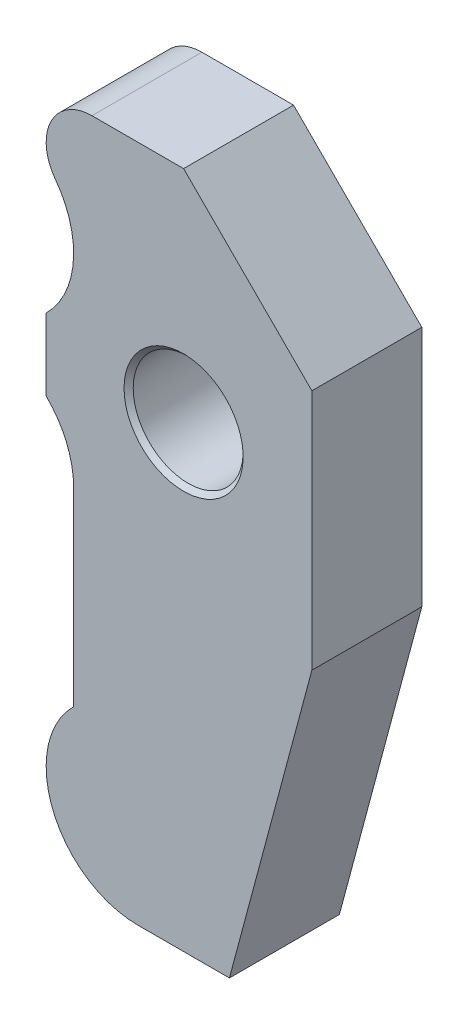
SolidWorks part; units mm, degrees
material "Простая углеродистая сталь"
ref_plane "Спереди" through (0, 0, 0) normal (0, 0, 1) x (1, 0, 0)
ref_plane "Сверху" through (0, 0, 0) normal (0, 1, 0) x (1, 0, 0)
ref_plane "Справа" through (0, 0, 0) normal (1, 0, 0) x (0, 0, -1)
sketch "Эскиз1" plane through (0, 0, 0) normal (0, 0, 1) x (1, 0, 0)
  line L0 (0, 24) -> (14, 10)
  line L1 (14, 10) -> (14, -16.4115)
  line L2 (14, -16.4115) -> (5, -50)
  line L3 (5, -50) -> (-5, -50)
  line L4 (-12, -32.8586) -> (-12, -12.1414)
  line L5 (-15, -5) -> (-15, 2.8586)
  line L6 (0, 24) -> (-10, 24)
  line L7 (5, -50) -> (5, -21.3258) construction
  circle A0 centre (0, 0) radius 6
  arc A1 (-5, -50) -> (-12, -32.8586) centre (-5, -40) cw
  arc A3 (-12, -12.1414) -> (-15, -5) centre (-22, -12.1414) ccw
  arc A4 (-15, 2.8586) -> (-14, 16) centre (-22, 10) ccw
  arc A5 (-14, 16) -> (-10, 24) centre (-10, 19) cw
  dimension "D1" = 10
  dimension "D3" = 10
  dimension "D4" = 5
  dimension "D11" = 12
  dimension "D12" = 10
  dimension "D13" = 5
  dimension "D2" = 3
  dimension "D5" = 15
  dimension "D6" = 45
  dimension "D7" = 15
  dimension "D8" = 40
  dimension "D9" = 19
  dimension "D10" = 29
  dimension "D14" = 5
extrude "Бобышка-Вытянуть1" add sketch "Эскиз1" along normal mid plane 12
chamfer "Фаска1" distance 0.5 angle 45 2 edges at (6, 0, -6) (6, 0, 6)
